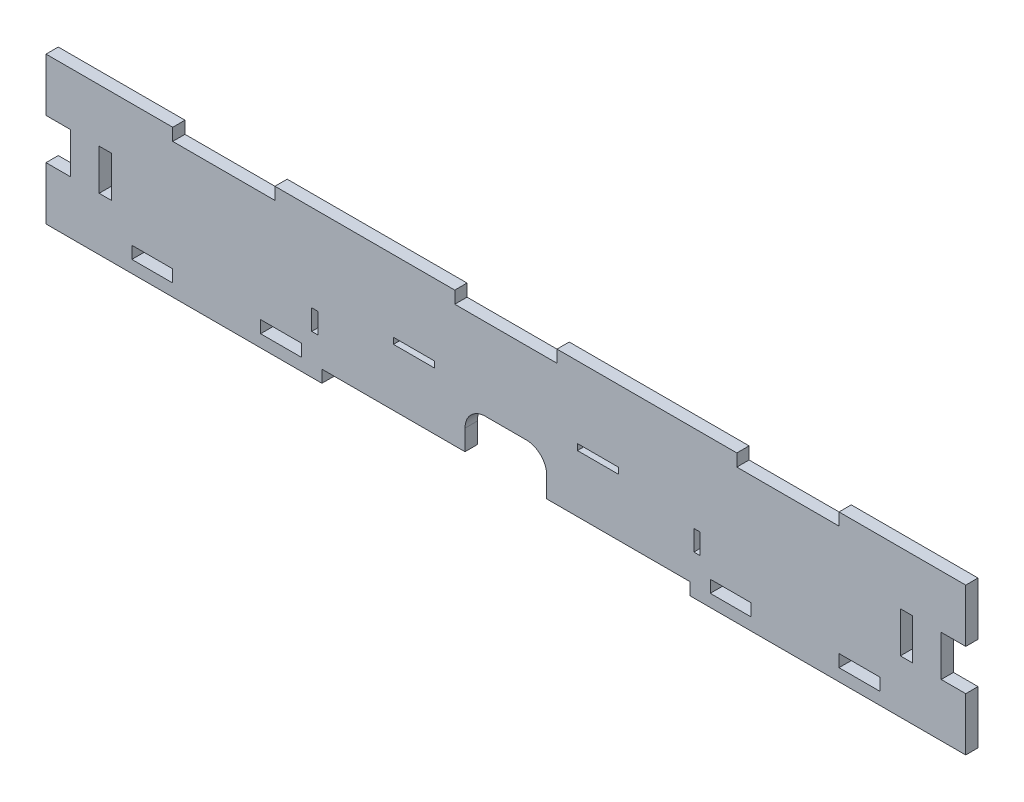
SolidWorks part; units mm, degrees
ref_plane "Спереди" through (0, 0, 0) normal (0, 0, 1) x (1, 0, 0)
ref_plane "Сверху" through (0, 0, 0) normal (0, 1, 0) x (1, 0, 0)
ref_plane "Справа" through (0, 0, 0) normal (1, 0, 0) x (0, 0, -1)
sketch "Эскиз1" plane through (0, 0, 0) normal (0, 0, 1) x (1, 0, 0)
  line L0 (0, 60) -> (0, 66)
  line L1 (0, 0) -> (450, 0) construction
  line L2 (0, 0) -> (0, 20)
  line L3 (62, 60) -> (112, 60)
  line L4 (450, 0) -> (450, 20)
  line L5 (0, 66) -> (62, 66)
  line L6 (62, 66) -> (62, 60)
  line L7 (112, 60) -> (112, 66)
  line L8 (112, 66) -> (200, 66)
  line L9 (200, 66) -> (200, 60)
  line L10 (250, 60) -> (250, 66)
  line L11 (250, 66) -> (338, 66)
  line L12 (338, 66) -> (338, 60)
  line L16 (388, 60) -> (388, 66)
  line L17 (388, 66) -> (450, 66)
  line L18 (450, 66) -> (450, 60)
  line L19 (0, 66) -> (450, 66) construction
  line L20 (200, 60) -> (250, 60)
  line L23 (0, 60) -> (450, 60) construction
  line L24 (105, 0) -> (105, 6)
  line L25 (105, 6) -> (125, 6)
  line L26 (125, 6) -> (125, 0)
  line L27 (205, 0) -> (205, 20)
  line L28 (205, 20) -> (245, 20)
  line L29 (245, 20) -> (245, 0)
  line L30 (245, 0) -> (315, 0)
  line L31 (325, 0) -> (325, 6)
  line L32 (325, 6) -> (345, 6)
  line L33 (345, 6) -> (345, 0)
  line L36 (135, 0) -> (205, 0)
  line L37 (58.3662, 6) -> (432.9281, 6) construction
  line L38 (0, 20) -> (12, 20)
  line L39 (12, 20) -> (12, 40)
  line L40 (12, 40) -> (0, 40)
  line L41 (450, 20) -> (438, 20)
  line L42 (26, 20) -> (32, 20)
  line L43 (26, 20) -> (26, 40)
  line L44 (26, 40) -> (32, 40)
  line L45 (32, 20) -> (32, 40)
  line L46 (438, 20) -> (438, 40)
  line L47 (438, 40) -> (450, 40)
  line L48 (0, 40) -> (0, 60)
  line L49 (424, 40) -> (418, 40)
  line L50 (424, 40) -> (424, 20)
  line L51 (424, 20) -> (418, 20)
  line L52 (418, 40) -> (418, 20)
  line L53 (450, 40) -> (450, 60)
  line L54 (338, 60) -> (388, 60)
  line L56 (105, 0) -> (125, 0)
  line L57 (0, 0) -> (0, -6)
  line L58 (0, -6) -> (135, -6)
  line L59 (135, 0) -> (135, -6)
  line L60 (345, 0) -> (325, 0)
  line L61 (450, 0) -> (450, -6)
  line L62 (450, -6) -> (315, -6)
  line L63 (315, 0) -> (315, -6)
  line L64 (388, 0) -> (408, 0)
  line L65 (388, 0) -> (388, 6)
  line L66 (388, 6) -> (408, 6)
  line L67 (408, 0) -> (408, 6)
  line L68 (62, 6) -> (42, 6)
  line L69 (62, 6) -> (62, 0)
  line L70 (62, 0) -> (42, 0)
  line L71 (42, 6) -> (42, 0)
  line L72 (320, 13.5) -> (317, 13.5)
  line L73 (320, 13.5) -> (320, 23.5)
  line L74 (320, 23.5) -> (317, 23.5)
  line L75 (317, 13.5) -> (317, 23.5)
  line L76 (130, 23.5) -> (133, 23.5)
  line L77 (130, 23.5) -> (130, 13.5)
  line L78 (130, 13.5) -> (133, 13.5)
  line L79 (133, 23.5) -> (133, 13.5)
  line L80 (170, 31) -> (190, 31)
  line L81 (170, 31) -> (170, 28)
  line L82 (170, 28) -> (190, 28)
  line L83 (190, 31) -> (190, 28)
  line L84 (260, 28) -> (280, 28)
  line L85 (260, 28) -> (260, 31)
  line L86 (260, 31) -> (280, 31)
  line L87 (280, 28) -> (280, 31)
  point P61 (225, 20)
  dimension "D1" = 450
  dimension "D2" = 60
  dimension "D3" = 66
  dimension "D4" = 62
  dimension "D5" = 50
  dimension "D6" = 88
  dimension "D7" = 50
  dimension "D8" = 88
  dimension "D9" = 180
  dimension "D10" = 135
  dimension "D11" = 62
  dimension "D12" = 6
  dimension "D13" = 20
  dimension "D14" = 20
  dimension "D15" = 20
  dimension "D16" = 20
  dimension "D17" = 40
  dimension "D18" = 90
  dimension "D19" = 14
  dimension "D20" = 20
  dimension "D21" = 12
  dimension "D22" = 6
  dimension "D23" = 6
  dimension "D24" = 12
  dimension "D25" = 14
  dimension "D26" = 14
  dimension "D27" = 6
  dimension "D28" = 100
  dimension "D29" = 20
  dimension "D30" = 43
  dimension "D31" = 100
  dimension "D32" = 43
  dimension "D33" = 10
  dimension "D34" = 130
  dimension "D35" = 3
  dimension "D36" = 7.5
  dimension "D37" = 3
  dimension "D38" = 130
  dimension "D39" = 7.5
  dimension "D40" = 3
  dimension "D41" = 20
  dimension "D42" = 20
  dimension "D43" = 37
  dimension "D44" = 70
extrude "Бобышка-Вытянуть1" add sketch "Эскиз1" along normal blind 6
fillet "Скругление1" radius 10 1 edges at (205, 20, 3)
fillet "Скругление2" radius 10 1 edges at (245, 20, 3)
